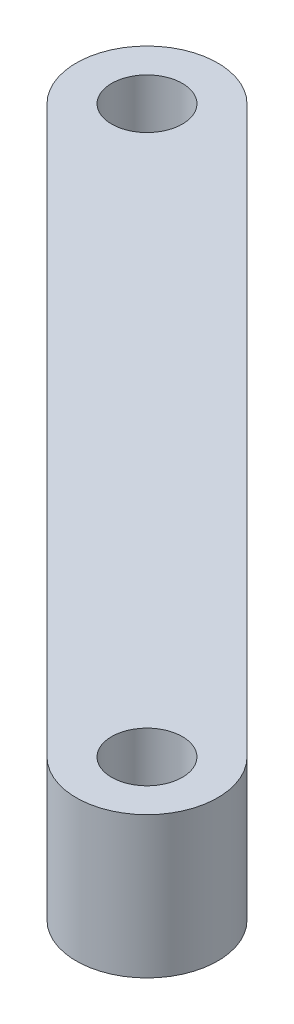
SolidWorks part; units mm, degrees
ref_plane "Front" through (0, 0, 0) normal (0, 0, 1) x (1, 0, 0)
ref_plane "Top" through (0, 0, 0) normal (0, 1, 0) x (1, 0, 0)
ref_plane "Right" through (0, 0, 0) normal (1, 0, 0) x (0, 0, -1)
sketch "Sketch1" plane through (0, 0, 0) normal (0, 1, 0) x (1, 0, 0)
  line L0 (-11.7678, 8.2322) -> (8.2322, -11.7678)
  line L1 (-12.5, -12.5) -> (12.5, -12.5) construction
  line L2 (-12.5, -12.5) -> (-12.5, 12.5) construction
  line L3 (-12.5, 12.5) -> (12.5, 12.5) construction
  line L4 (12.5, -12.5) -> (12.5, 12.5) construction
  line L5 (-12.5, -12.5) -> (12.5, 12.5) construction
  line L6 (-12.5, 12.5) -> (12.5, -12.5) construction
  line L7 (-10, -10) -> (10, -10) construction
  line L8 (-10, -10) -> (-10, 10) construction
  line L9 (-10, 10) -> (10, 10) construction
  line L10 (10, -10) -> (10, 10) construction
  line L11 (-10, -10) -> (10, 10) construction
  line L12 (-10, 10) -> (10, -10) construction
  line L13 (11.7678, -8.2322) -> (-8.2322, 11.7678)
  circle A0 centre (-10, 10) radius 2.5 construction
  circle A1 centre (10, -10) radius 2.5 construction
  arc A2 (-11.7678, 8.2322) -> (-8.2322, 11.7678) centre (-10, 10) cw
  arc A3 (11.7678, -8.2322) -> (8.2322, -11.7678) centre (10, -10) cw
  point P0 (0, 0)
  point P7 (0, 0)
  dimension "D1" = 25
  dimension "D3" = 20
extrude "Boss-Extrude1" add sketch "Sketch1" along normal blind 5
sketch "Sketch2" plane through (0, 5, 0) normal (0, 1, 0) x (1, 0, 0)
  circle A0 centre (-10, 10) radius 1.25
  circle A1 centre (10, -10) radius 1.25
  arc A2 (-8.2322, 11.7678) -> (-11.7678, 8.2322) centre (-10, 10) ccw construction
  dimension "D1" = 2.5
extrude "Cut-Extrude1" cut sketch "Sketch2" against normal through all
